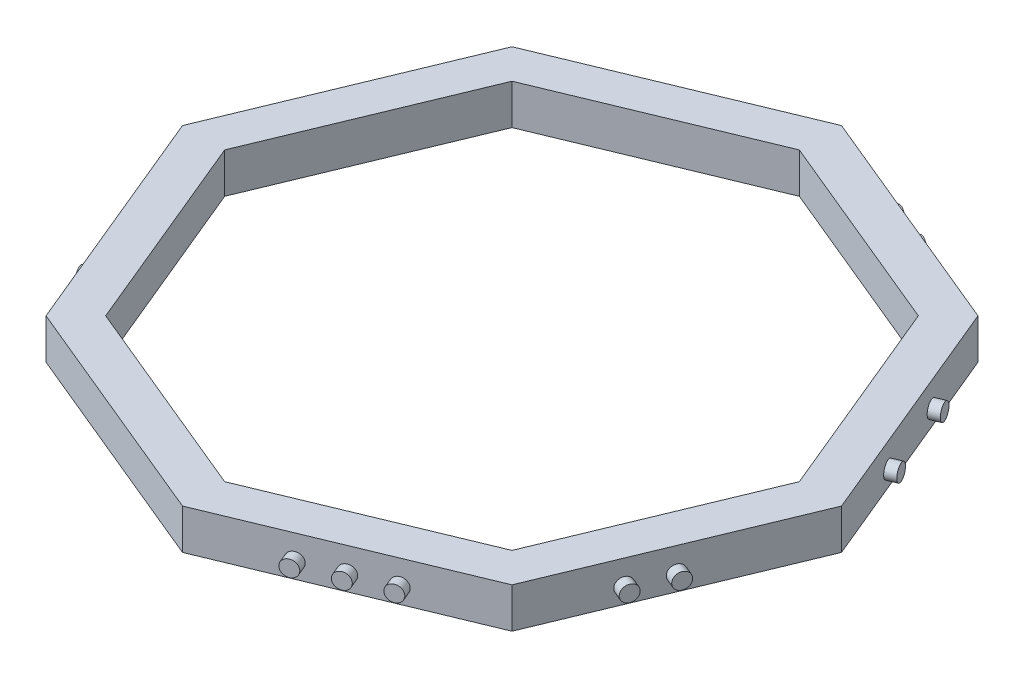
SolidWorks part; units mm, degrees
ref_plane "Front Plane" through (0, 0, 0) normal (0, 0, 1) x (1, 0, 0)
ref_plane "Top Plane" through (0, 0, 0) normal (0, 1, 0) x (1, 0, 0)
ref_plane "Right Plane" through (0, 0, 0) normal (1, 0, 0) x (0, 0, -1)
sketch "Sketch3" plane through (0, 0, 0) normal (0, 1, 0) x (1, 0, 0)
  line L1 (41, 0) -> (28.9914, 28.9914)
  line L2 (28.9914, 28.9914) -> (0, 41)
  line L3 (0, 41) -> (-28.9914, 28.9914)
  line L4 (-28.9914, 28.9914) -> (-41, 0)
  line L5 (-41, 0) -> (-28.9914, -28.9914)
  line L6 (-28.9914, -28.9914) -> (0, -41)
  line L7 (0, -41) -> (28.9914, -28.9914)
  line L8 (28.9914, -28.9914) -> (41, 0)
  circle A0 centre (0, 0) radius 37.8791 construction
  dimension "D1" = 41
extrude "Boss-Extrude1" add sketch "Sketch3" along normal blind 5
sketch "Sketch5" plane through (0, 5, 0) normal (0, 1, 0) x (1, 0, 0)
  line L1 (35.75, 0) -> (25.2791, 25.2791)
  line L2 (25.2791, 25.2791) -> (0, 35.75)
  line L3 (0, 35.75) -> (-25.2791, 25.2791)
  line L4 (-25.2791, 25.2791) -> (-35.75, 0)
  line L5 (-35.75, 0) -> (-25.2791, -25.2791)
  line L6 (-25.2791, -25.2791) -> (0, -35.75)
  line L7 (0, -35.75) -> (25.2791, -25.2791)
  line L8 (25.2791, -25.2791) -> (35.75, 0)
  circle A0 centre (0, 0) radius 33.0287 construction
  dimension "D2" = 41
  dimension "D1" = 35.75
extrude "Cut-Extrude1" cut sketch "Sketch5" against normal blind 5
sketch "Sketch6" plane through (14.4957, 0, 34.9957) normal (0.3827, 0, 0.9239) x (0.9239, 0, -0.3827)
  circle A0 centre (0, 2) radius 1
  circle A1 centre (-5, 2) radius 1
  circle A2 centre (5, 2) radius 1
sketch "Sketch7" plane through (-34.9957, 0, 14.4957) normal (-0.9239, 0, 0.3827) x (0.3827, 0, 0.9239)
  circle A0 centre (5, 2) radius 1
sketch "Sketch8" plane through (-34.9957, 0, -14.4957) normal (-0.9239, 0, -0.3827) x (-0.3827, 0, 0.9239)
  circle A0 centre (0, 2) radius 1
sketch "Sketch9" plane through (-14.4957, 0, -34.9957) normal (-0.3827, 0, -0.9239) x (-0.9239, 0, 0.3827)
  circle A0 centre (-5, 2) radius 1
sketch "Sketch10" plane through (14.4957, 0, -34.9957) normal (0.3827, 0, -0.9239) x (-0.9239, 0, -0.3827)
  circle A0 centre (0, 2) radius 1
  circle A1 centre (5, 2) radius 1
sketch "Sketch11" plane through (34.9957, 0, -14.4957) normal (0.9239, 0, -0.3827) x (-0.3827, 0, -0.9239)
  circle A0 centre (5, 2) radius 1
  circle A1 centre (-5, 2) radius 1
sketch "Sketch12" plane through (34.9957, 0, 14.4957) normal (0.9239, 0, 0.3827) x (0.3827, 0, -0.9239)
  circle A0 centre (0, 2) radius 1
  circle A1 centre (-5, 2) radius 1
extrude "Boss-Extrude5" add sketch "Sketch6" along normal blind 1.25 contours A2 | A1 | A0
extrude "Boss-Extrude6" add sketch "Sketch7" along normal blind 1.25 contours A0
extrude "Boss-Extrude7" add sketch "Sketch8" along normal blind 1.25 contours A0
extrude "Boss-Extrude8" add sketch "Sketch9" along normal blind 1.25 contours A0
extrude "Boss-Extrude9" add sketch "Sketch10" along normal blind 1.25 contours A0 | A1
extrude "Boss-Extrude10" add sketch "Sketch11" along normal blind 1.25 contours A1 | A0
extrude "Boss-Extrude11" add sketch "Sketch12" along normal blind 1.25 contours A1 | A0
